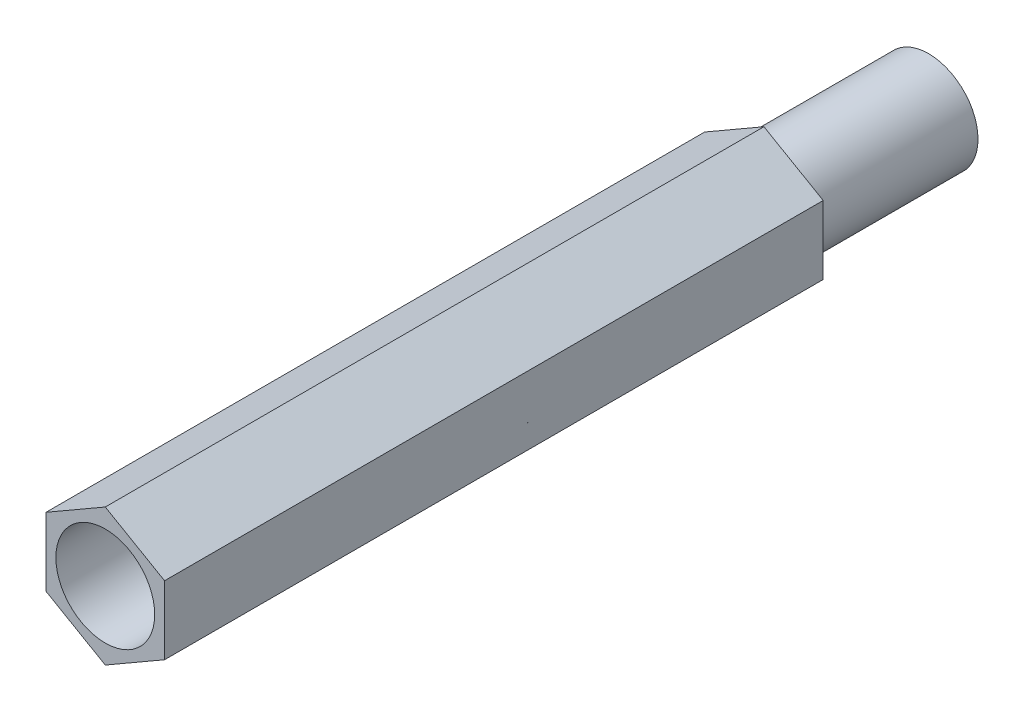
SolidWorks part; units mm, degrees
ref_plane "前视基准面" through (0, 0, 0) normal (0, 0, 1) x (1, 0, 0)
ref_plane "上视基准面" through (0, 0, 0) normal (0, 1, 0) x (1, 0, 0)
ref_plane "右视基准面" through (0, 0, 0) normal (1, 0, 0) x (0, 0, -1)
sketch "草图1" plane through (0, 0, 0) normal (0, 0, 1) x (1, 0, 0)
  line L1 (0, 2.0785) -> (-1.8, 1.0392)
  line L2 (-1.8, 1.0392) -> (-1.8, -1.0392)
  line L3 (-1.8, -1.0392) -> (0, -2.0785)
  line L4 (0, -2.0785) -> (1.8, -1.0392)
  line L5 (1.8, -1.0392) -> (1.8, 1.0392)
  line L6 (1.8, 1.0392) -> (0, 2.0785)
  circle A0 centre (0, 0) radius 1.8 construction
  circle A1 centre (0, 0) radius 1.5
extrude "凸台-拉伸1" add sketch "草图1" along normal blind 20
sketch "草图2" plane through (0, 0, 0) normal (0, 0, -1) x (-1, 0, 0)
  circle A0 centre (0, 0) radius 1.5
extrude "凸台-拉伸2" add sketch "草图2" along normal mid plane 10 contours A0
